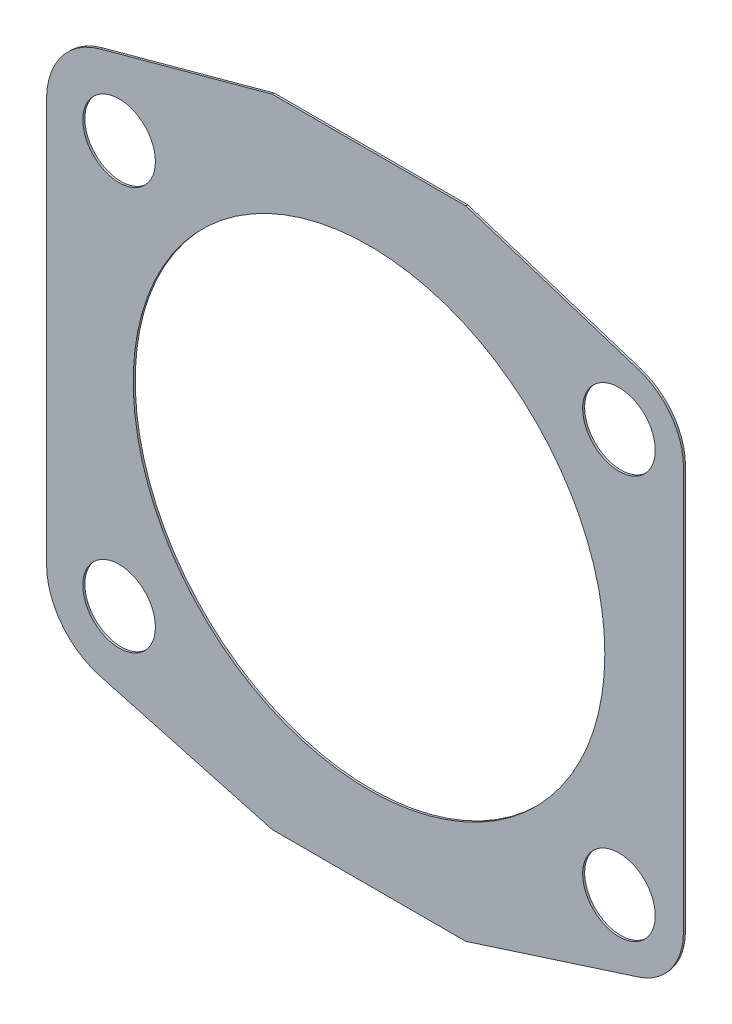
SolidWorks part; units mm, degrees
material "TESNIT BA-GL"
ref_plane "Front Plane" through (0, 0, 0) normal (0, 0, 1) x (1, 0, 0)
ref_plane "Top Plane" through (0, 0, 0) normal (0, 1, 0) x (1, 0, 0)
ref_plane "Right Plane" through (0, 0, 0) normal (1, 0, 0) x (0, 0, -1)
sketch "Sketch1" plane through (0, 0, 0) normal (0, 0, 1) x (1, 0, 0)
  line L0 (0, 0) -> (104.5323, 0) construction
  line L1 (0, 0) -> (0, 55.1293) construction
  line L16 (-66.7281, -67.3679) -> (-24, -79)
  line L17 (-24, -79) -> (24, -79)
  line L18 (24, -79) -> (66.8895, -65.2346)
  line L19 (78, -50) -> (78, 50)
  line L20 (66.8895, 65.2346) -> (24, 79)
  line L21 (24, 79) -> (-24, 79)
  line L22 (-24, 79) -> (-66.7281, 67.3679)
  line L23 (-80, 50) -> (-80, -50)
  circle A1 centre (0, 0) radius 58.5
  arc A8 (66.8895, -65.2346) -> (78, -50) centre (62, -50) ccw
  arc A9 (78, 50) -> (66.8895, 65.2346) centre (62, 50) ccw
  arc A10 (-66.7281, 67.3679) -> (-80, 50) centre (-62, 50) ccw
  arc A11 (-80, -50) -> (-66.7281, -67.3679) centre (-62, -50) ccw
  circle A14 centre (62, -50) radius 9
  circle A15 centre (-62, -50) radius 9
  circle A16 centre (62, 50) radius 9
  circle A17 centre (-62, 50) radius 9
  dimension "D1" = 124
  dimension "D2" = 100
  dimension "D3" = 18
  dimension "D4" = 18
  dimension "D8" = 117
  dimension "D5" = 48
  dimension "D6" = 158
  dimension "D7" = 158
extrude "Extrude1" add sketch "Sketch1" along normal blind 0.5
